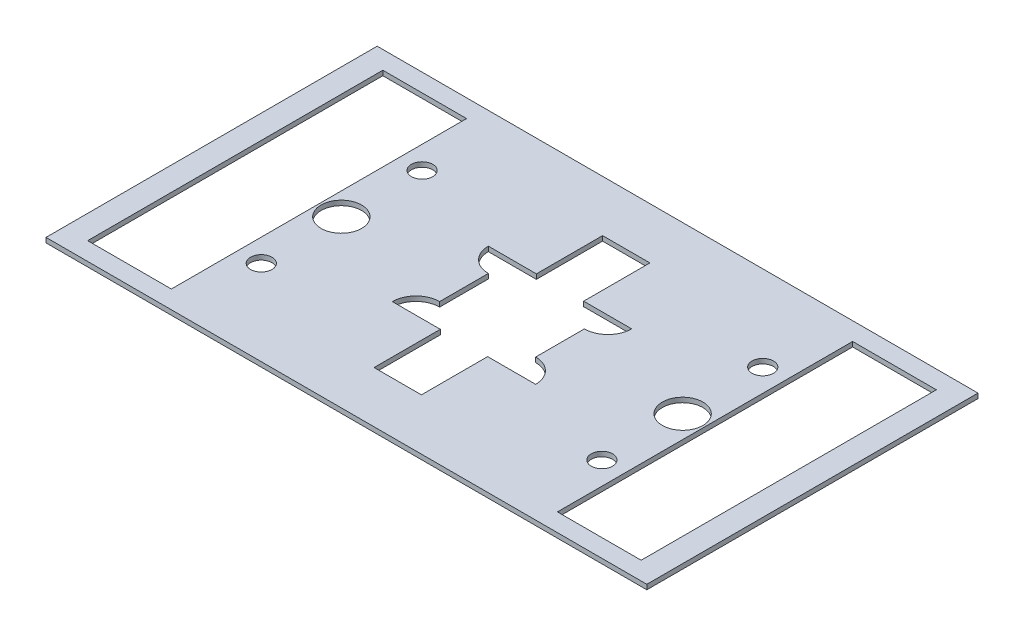
SolidWorks part; units mm, degrees
material "Copper"
ref_plane "Front Plane" through (0, 0, 0) normal (0, 0, 1) x (1, 0, 0)
ref_plane "Top Plane" through (0, 0, 0) normal (0, 1, 0) x (1, 0, 0)
ref_plane "Right Plane" through (0, 0, 0) normal (1, 0, 0) x (0, 0, -1)
sketch "Sketch1" plane through (0, 0, 0) normal (0, 1, 0) x (1, 0, 0)
  line L0 (-2.5, 5.075) -> (-2.5, 12.075)
  line L1 (-5, 5) -> (5, 5) construction
  line L2 (-5, 5) -> (-5, -5) construction
  line L3 (-5, -5) -> (5, -5) construction
  line L4 (5, 5) -> (5, -5) construction
  line L5 (-5.075, 5.075) -> (5.075, 5.075)
  line L6 (-5.075, 5.075) -> (-5.075, -5.075)
  line L7 (-5.075, -5.075) -> (5.075, -5.075)
  line L8 (5.075, 5.075) -> (5.075, -5.075)
  line L9 (-7.575, 7.575) -> (7.575, 7.575)
  line L10 (-7.575, 7.575) -> (-7.575, -7.575)
  line L11 (-7.575, -7.575) -> (7.575, -7.575)
  line L12 (7.575, 7.575) -> (7.575, -7.575)
  line L13 (-31.75, 17.75) -> (31.75, 17.75) construction
  line L14 (-31.75, 17.75) -> (-31.75, -17.75) construction
  line L15 (-31.75, -17.75) -> (31.75, -17.75) construction
  line L16 (31.75, 17.75) -> (31.75, -17.75) construction
  line L17 (-31.75, 17.5) -> (31.75, 17.5)
  line L18 (-31.75, 17.5) -> (-31.75, -17.5)
  line L19 (-31.75, -17.5) -> (31.75, -17.5)
  line L20 (31.75, 17.5) -> (31.75, -17.5)
  line L21 (-29.25, 15.6) -> (-20.4, 15.6)
  line L22 (-29.25, 15.6) -> (-29.25, -15.6)
  line L23 (-29.25, -15.6) -> (-20.4, -15.6)
  line L24 (-20.4, 15.6) -> (-20.4, -15.6)
  line L25 (20.4, 15.6) -> (29.25, 15.6)
  line L26 (20.4, 15.6) -> (20.4, -15.6)
  line L27 (20.4, -15.6) -> (29.25, -15.6)
  line L28 (29.25, 15.6) -> (29.25, -15.6)
  line L29 (-2.5, 12.075) -> (2.5, 12.075)
  line L30 (2.5, 12.075) -> (2.5, 5.075)
  line L31 (-2.5, -5.075) -> (-2.5, -12.075)
  line L32 (-2.5, -12.075) -> (2.5, -12.075)
  line L33 (2.5, -12.075) -> (2.5, -5.075)
  line L34 (-5.075, 5.075) -> (-5.075, 7.575)
  line L35 (5.075, 5.075) -> (5.075, 7.575)
  line L36 (5.075, -5.075) -> (5.075, -7.575)
  line L37 (-5.075, -5.075) -> (-5.075, -7.575)
  line L38 (-5.075, 5.075) -> (-7.575, 5.075)
  line L39 (5.075, 5.075) -> (7.575, 5.075)
  line L40 (-5.075, -5.075) -> (-7.575, -5.075)
  line L41 (5.075, -5.075) -> (7.575, -5.075)
  circle A0 centre (-5.075, 5.075) radius 2.5
  circle A1 centre (5.075, 5.075) radius 2.5
  circle A2 centre (5.075, -5.075) radius 2.5
  circle A3 centre (-5.075, -5.075) radius 2.5
  circle A4 centre (-18, 8.5) radius 1.13
  circle A5 centre (18, 8.5) radius 1.13
  circle A6 centre (18, -8.5) radius 1.13
  circle A7 centre (-18, -8.5) radius 1.13
  circle A8 centre (-18.034, 0) radius 2.1446
  circle A9 centre (18.034, 0) radius 2.1446
  point P4 (0, 5.075)
  point P13 (5.075, 0)
  point P14 (0, 5)
  point P16 (5, 0)
  point P25 (0, 17.75)
  point P26 (0, 7.575)
  point P31 (7.575, 0)
  point P32 (31.75, 0)
  point P37 (0, 17.5)
  point P38 (31.75, 0)
  point P47 (-29.25, 0)
  point P48 (-31.75, 0)
  point P63 (0, 12.075)
  point P72 (0, -12.075)
  dimension "D3" = 5
  dimension "D18" = 2.26
  dimension "D21" = 4.2892
  dimension "D1" = 10
  dimension "D2" = 10.15
  dimension "D4" = 35.5
  dimension "D5" = 63.5
  dimension "D6" = 63.5
  dimension "D7" = 35
  dimension "D8" = 2.15
  dimension "D10" = 31.2
  dimension "D11" = 8.85
  dimension "D12" = 2.15
  dimension "D14" = 18
  dimension "D15" = 8.5
  dimension "D16" = 8.5
  dimension "D17" = 18
  dimension "D19" = 18.034
  dimension "D20" = 18.034
  dimension "D22" = 5
  dimension "D23" = 7
  dimension "D24" = 7
  dimension "D13" = 2.5
  dimension "D9" = 2.5
extrude "Boss-Extrude1" add sketch "Sketch1" along normal blind 0.508 contours L20 L17 L18 L19 A9 A8 A7 A6 A5 A4 L9 L12 L11 L10 L21 L24 L23 L22 L25 L28 L27 L26 | A2 L11 L12 | A2 L12 A1 L8 | A1 L12 L9 | A0 L9 L10 | A3 L6 A0 L10 | A3 L10 L11 | A0 L5 L0 L9 | A1 L9 L30 L5 | A2 L7 L33 L11 | A3 L11 L31 L7 | L5 A0 L34 | L35 A1 L5 | L7 A2 L36 | L37 A3 L7 | L34 A0 L38 | L39 A1 L35 | L36 A2 L8 | L40 A3 L37
equation "\"D2@Sketch1\"=\"D1@Sketch1\"+0.15"
equation "\"D17@Sketch1\"=\"D14@Sketch1\""
equation "\"D20@Sketch1\"=\"D19@Sketch1\""
equation "\"D24@Sketch1\"=\"D23@Sketch1\""
equation "\"D9@Sketch1\"=\"D13@Sketch1\""
